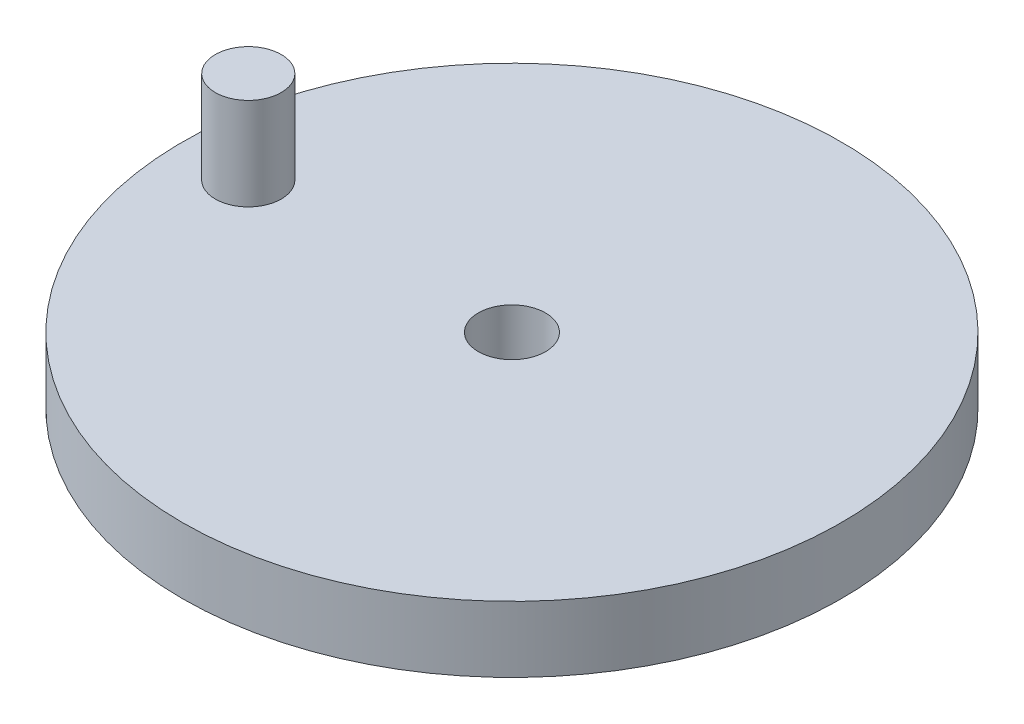
SolidWorks part; units mm, degrees
ref_plane "前基準面" through (0, 0, 0) normal (0, 0, 1) x (1, 0, 0)
ref_plane "上基準面" through (0, 0, 0) normal (0, 1, 0) x (1, 0, 0)
ref_plane "右基準面" through (0, 0, 0) normal (1, 0, 0) x (0, 0, -1)
sketch "草圖1" plane through (0, 0, 0) normal (0, 1, 0) x (1, 0, 0)
  line L0 (0, 25) -> (0, -25) construction
  line L1 (0, -25) -> (0, 0) construction
  line L2 (0, 0) -> (-25, 0) construction
  circle A0 centre (0, 0) radius 25
  circle A1 centre (0, 0) radius 2.55
  point P8 (0, 0)
  dimension "D1" = 50
  dimension "D2" = 5.1
extrude "填料-伸長1" add sketch "草圖1" along normal blind 5
sketch "草圖2" plane through (0, 5, 0) normal (0, 1, 0) x (1, 0, 0)
  line L0 (0, 25) -> (0, -25) construction
  line L1 (0, -25) -> (0, 0) construction
  line L2 (0, 0) -> (-25, 0) construction
  circle A0 centre (0, 0) radius 25 construction
  circle A1 centre (-20, 0) radius 2.5
  dimension "D2" = 5
  dimension "D1" = 20
extrude "填料-伸長2" add sketch "草圖2" along normal blind 7
